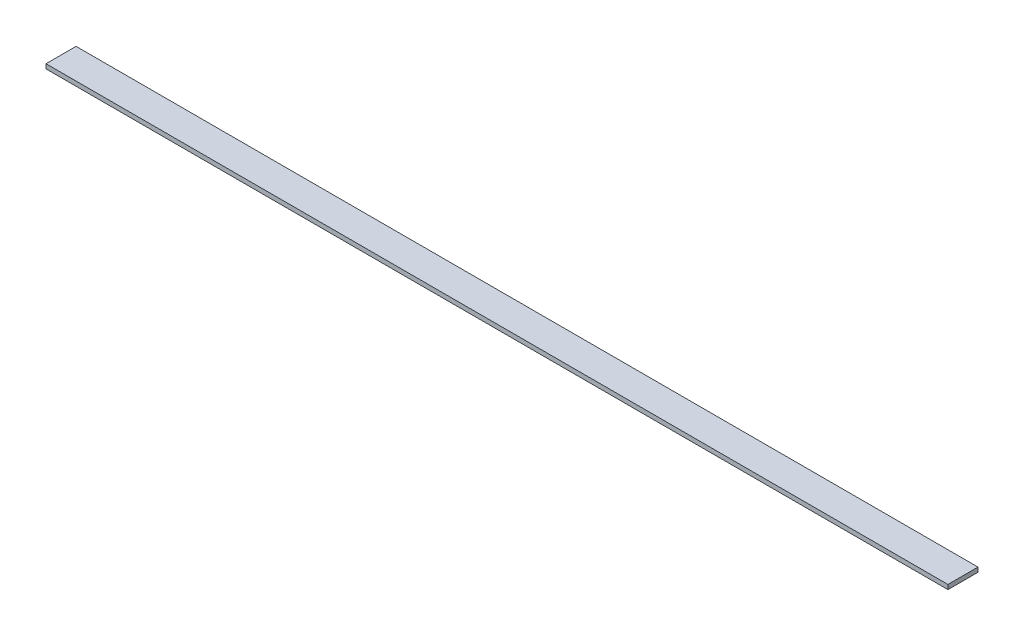
SolidWorks part; units mm, degrees
ref_plane "Front Plane" through (0, 0, 0) normal (0, 0, 1) x (1, 0, 0)
ref_plane "Top Plane" through (0, 0, 0) normal (0, 1, 0) x (1, 0, 0)
ref_plane "Right Plane" through (0, 0, 0) normal (1, 0, 0) x (0, 0, -1)
sketch "Sketch1" plane through (0, 0, 0) normal (0, 1, 0) x (1, 0, 0)
  line L1 (223.7059, 210.2762) -> (-376.2941, 210.2762)
  line L2 (223.7059, 210.2762) -> (223.7059, 230.2762)
  line L3 (223.7059, 230.2762) -> (-376.2941, 230.2762)
  line L4 (-376.2941, 210.2762) -> (-376.2941, 230.2762)
  dimension "D1" = 600
  dimension "D2" = 20
extrude "Boss-Extrude1" add sketch "Sketch1" along normal blind 3
